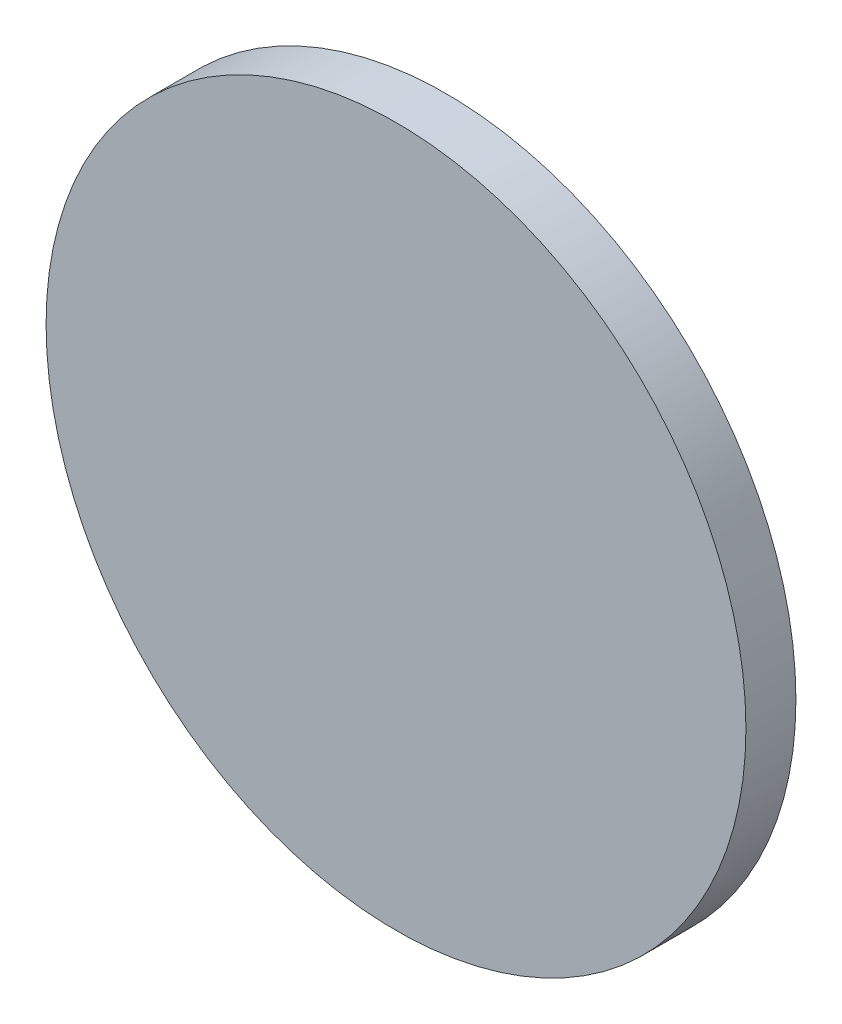
SolidWorks part; units mm, degrees
ref_plane "Front Plane" through (0, 0, 0) normal (0, 0, 1) x (1, 0, 0)
ref_plane "Top Plane" through (0, 0, 0) normal (0, 1, 0) x (1, 0, 0)
ref_plane "Right Plane" through (0, 0, 0) normal (1, 0, 0) x (0, 0, -1)
sketch "Sketch1" plane through (0, 0, 0) normal (0, 0, 1) x (1, 0, 0)
  circle A0 centre (0, 0) radius 7
  dimension "D1" = 14
extrude "Boss-Extrude1" add sketch "Sketch1" along normal blind 1
